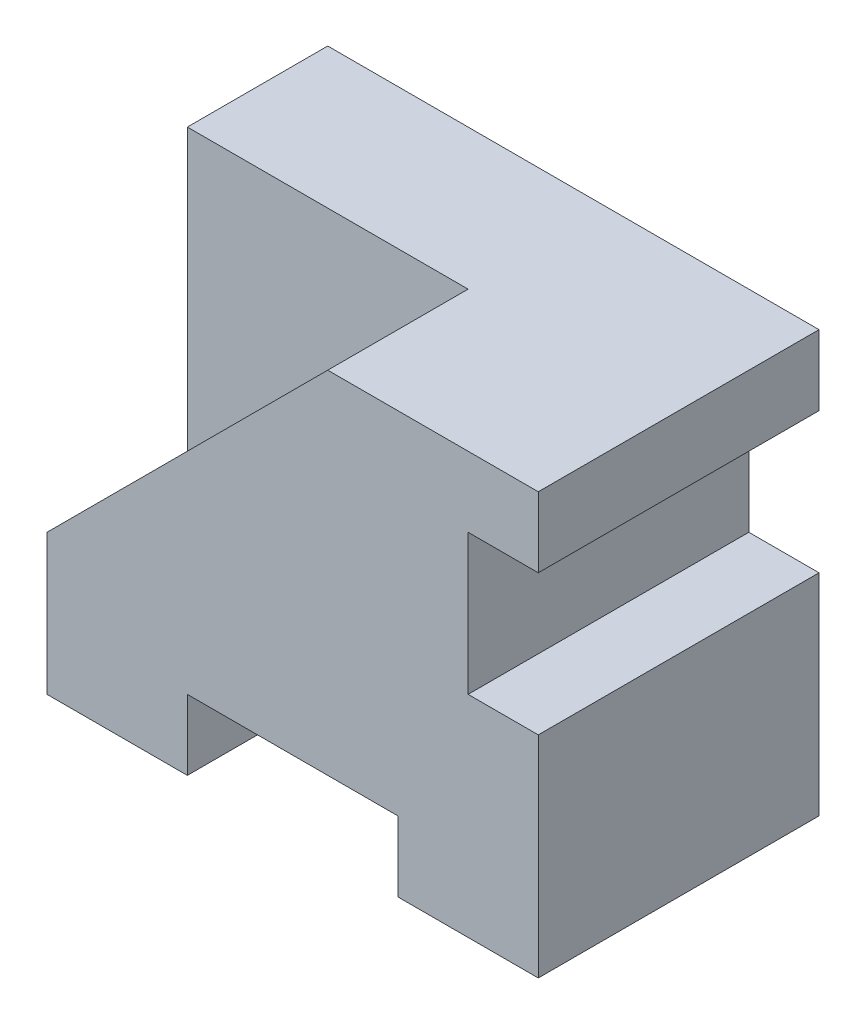
SolidWorks part; units mm, degrees
ref_plane "Front Plane" through (0, 0, 0) normal (0, 0, 1) x (1, 0, 0)
ref_plane "Top Plane" through (0, 0, 0) normal (0, 1, 0) x (1, 0, 0)
ref_plane "Right Plane" through (0, 0, 0) normal (1, 0, 0) x (0, 0, -1)
sketch "Sketch1" plane through (0, 0, 0) normal (0, 1, 0) x (1, 0, 0)
  line L1 (-35, -20) -> (35, -20)
  line L2 (-35, -20) -> (-35, 20)
  line L3 (-35, 20) -> (35, 20)
  line L4 (35, -20) -> (35, 20)
  line L5 (-35, -20) -> (35, 20) construction
  line L6 (-35, 20) -> (35, -20) construction
  point P0 (0, 0)
  dimension "D1" = 70
  dimension "D2" = 40
extrude "Boss-Extrude1" add sketch "Sketch1" along normal blind 60
sketch "Sketch2" plane through (0, 0, 20) normal (0, 0, 1) x (1, 0, 0)
  line L0 (-15, 62.9725) -> (-15, -4.7245) construction
  line L1 (15, 66.4906) -> (15, -16.4772) construction
  line L2 (-53.8062, 10) -> (47.9447, 10) construction
  line L3 (-15, 0) -> (-15, 10)
  line L4 (-35, 0) -> (35, 0) construction
  line L5 (-15, 10) -> (15, 10)
  line L6 (15, 10) -> (15, 0)
  line L7 (15, 0) -> (-15, 0)
  dimension "D1" = 20
  dimension "D2" = 20
  dimension "D3" = 10
  dimension "D4" = 10
extrude "Cut-Extrude1" cut sketch "Sketch2" against normal through all
sketch "Sketch3" plane through (0, 0, 20) normal (0, 0, 1) x (1, 0, 0)
  line L0 (-49.8596, 30) -> (48.6245, 30) construction
  line L1 (25, 65.898) -> (25, -14.4774) construction
  line L2 (-52.5063, 50) -> (52.107, 50) construction
  line L3 (35, 50) -> (25, 50)
  line L4 (35, 60) -> (35, 0) construction
  line L5 (25, 50) -> (25, 30)
  line L6 (25, 30) -> (35, 30)
  line L7 (35, 30) -> (35, 50)
  dimension "D1" = 30
  dimension "D2" = 10
  dimension "D3" = 10
extrude "Cut-Extrude2" cut sketch "Sketch3" against normal through all
sketch "Sketch4" plane through (0, 0, 20) normal (0, 0, 1) x (1, 0, 0)
  line L0 (-46.1009, 20) -> (45.1637, 20) construction
  line L1 (5, 67.133) -> (5, -9.2059) construction
  line L4 (-35, 20) -> (5, 60)
  line L6 (-35, 60) -> (-35, 0) construction
  dimension "D1" = 20
  dimension "D2" = 30
  dimension "D3" = 40
extrude "Cut-Extrude3" cut sketch "Sketch4" against normal blind 20 and the other way through all
